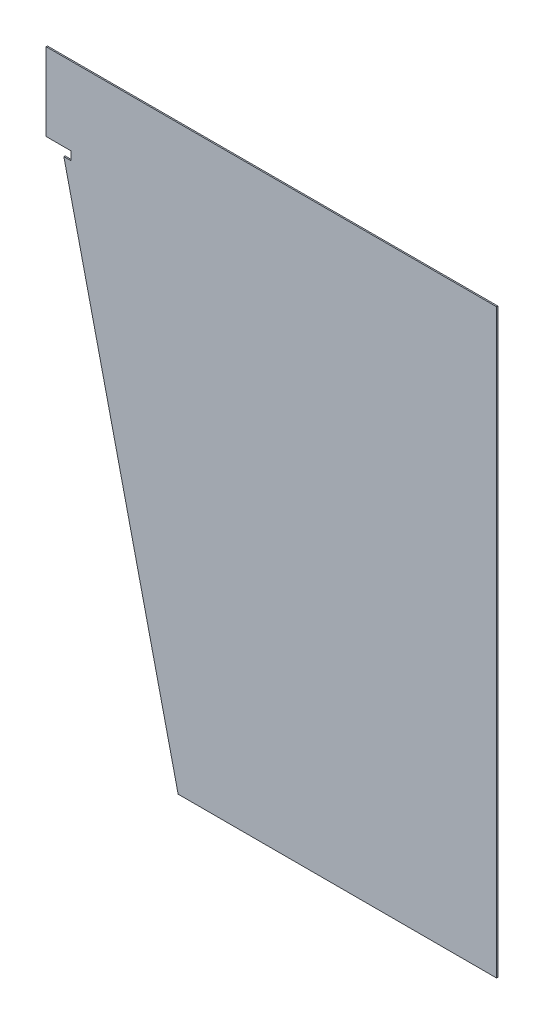
SolidWorks part; units mm, degrees
ref_plane "Alzado" through (0, 0, 0) normal (0, 0, 1) x (1, 0, 0)
ref_plane "Planta" through (0, 0, 0) normal (0, 1, 0) x (1, 0, 0)
ref_plane "Vista lateral" through (0, 0, 0) normal (1, 0, 0) x (0, 0, -1)
sketch "Croquis1" plane through (0, 0, 0) normal (0, 0, 1) x (1, 0, 0)
  line L0 (0, 0) -> (0, -115.76)
  line L1 (0, -115.76) -> (37, -115.76)
  line L2 (37, -115.76) -> (37, -128.46)
  line L3 (37, -128.46) -> (26.24, -128.46)
  line L4 (26.24, -128.46) -> (196.2837, -865)
  line L5 (196.2837, -865) -> (670, -865)
  line L6 (670, -865) -> (670, 0)
  line L7 (670, 0) -> (0, 0)
  dimension "D1" = 115.76
  dimension "D2" = 37
  dimension "D3" = 12.7
  dimension "D4" = 10.76
  dimension "D5" = 77
  dimension "D6" = 865
  dimension "D7" = 670
extrude "Saliente-Extruir1" add sketch "Croquis1" along normal blind 1.9
